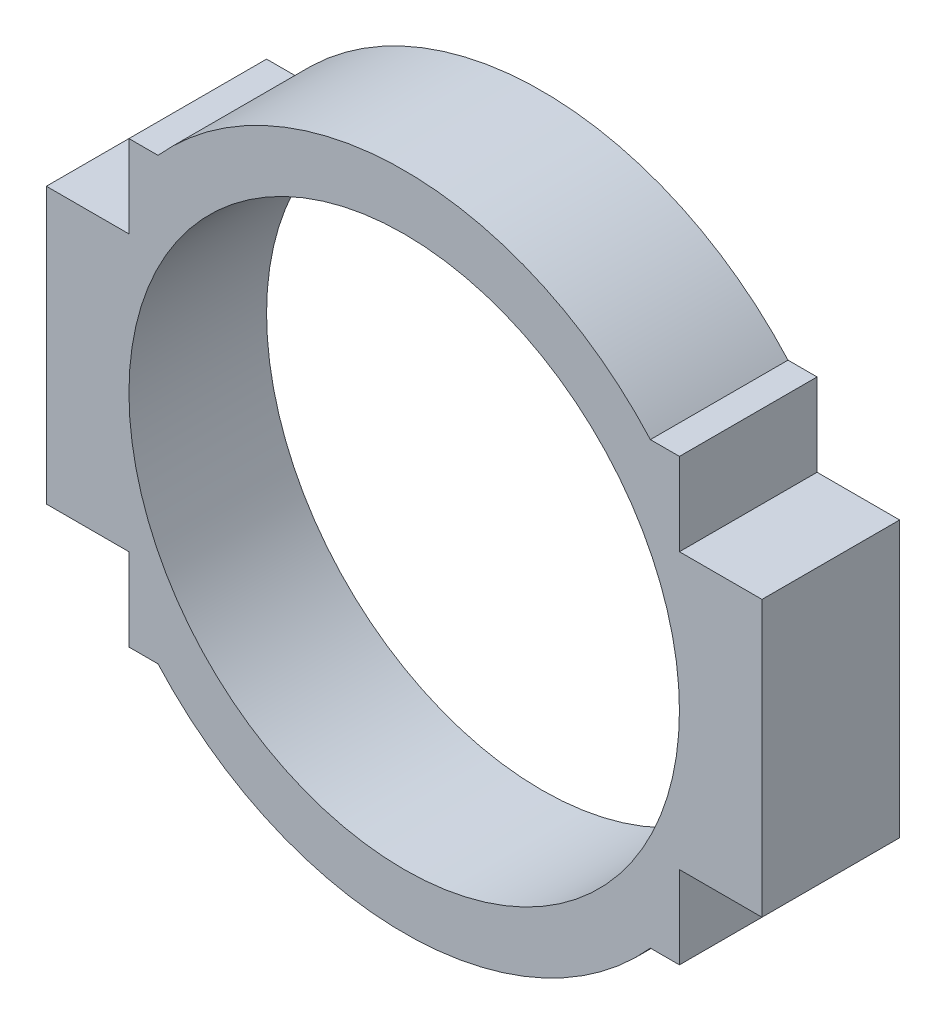
SolidWorks part; units mm, degrees
ref_plane "前视基准面" through (0, 0, 0) normal (0, 0, 1) x (1, 0, 0)
ref_plane "上视基准面" through (0, 0, 0) normal (0, 1, 0) x (1, 0, 0)
ref_plane "右视基准面" through (0, 0, 0) normal (1, 0, 0) x (0, 0, -1)
sketch "草图1" plane through (0, 0, 0) normal (0, 0, 1) x (1, 0, 0)
  line L10 (13, -5) -> (10, -5)
  line L18 (10, -5) -> (10, -8)
  line L19 (-13, -5) -> (-13, 5)
  line L20 (-13, 5) -> (-10, 5)
  line L21 (-10, 5) -> (-10, 8)
  line L22 (-10, 8) -> (-8.9443, 8)
  line L25 (-10, -8) -> (-8.9443, -8)
  line L26 (-10, -5) -> (-10, -8)
  line L27 (-13, -5) -> (-10, -5)
  line L28 (10, -8) -> (8.9443, -8)
  line L29 (10, 8) -> (8.9443, 8)
  line L30 (10, 5) -> (10, 8)
  line L31 (13, 5) -> (10, 5)
  line L32 (13, -5) -> (13, 5)
  circle A0 centre (0, 0) radius 10
  arc A5 (-8.9443, 8) -> (8.9443, 8) centre (0, 0) cw
  arc A6 (-8.9443, -8) -> (8.9443, -8) centre (0, 0) ccw
extrude "凸台-拉伸1" add sketch "草图1" along normal blind 5
